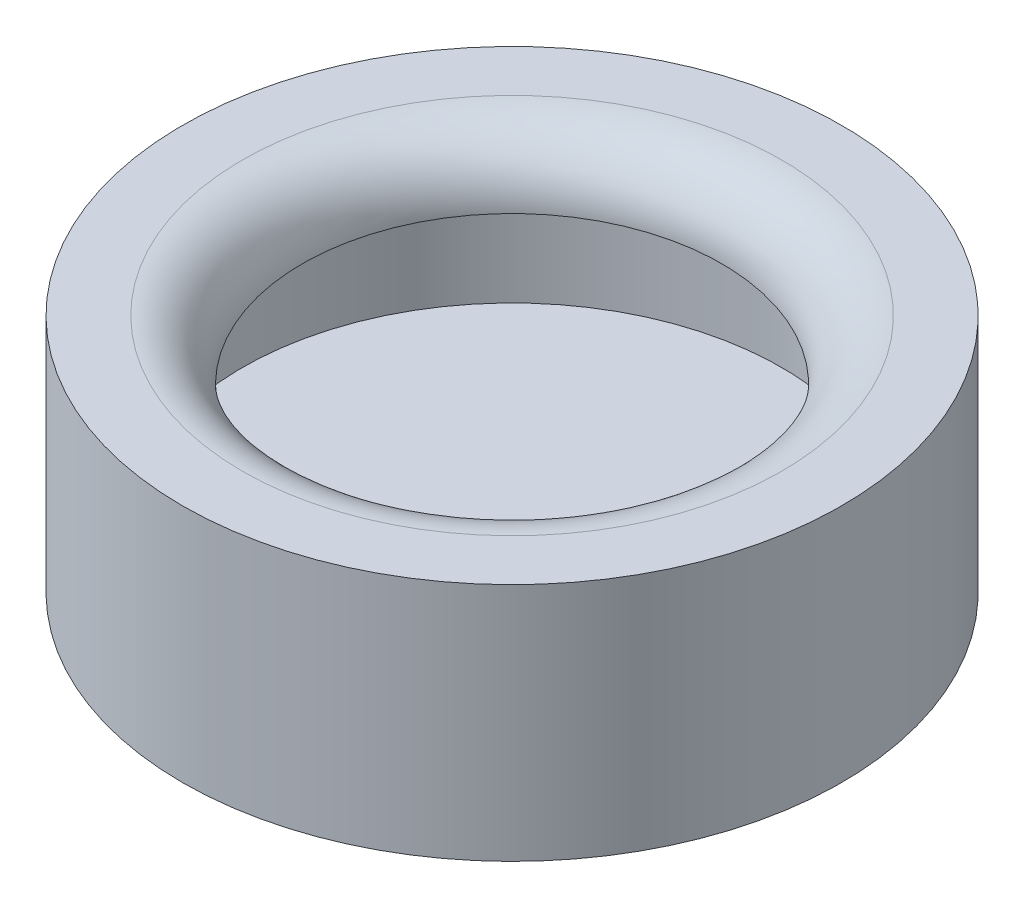
SolidWorks part; units mm, degrees
ref_plane "Front Plane" through (0, 0, 0) normal (0, 0, 1) x (1, 0, 0)
ref_plane "Top Plane" through (0, 0, 0) normal (0, 1, 0) x (1, 0, 0)
ref_plane "Right Plane" through (0, 0, 0) normal (1, 0, 0) x (0, 0, -1)
sketch "Sketch1" plane through (0, 0, 0) normal (0, 1, 0) x (1, 0, 0)
  circle A0 centre (0, 0) radius 6.985
  dimension "D1" = 13.97
extrude "Boss-Extrude1" add sketch "Sketch1" along normal blind 5.08
sketch "Sketch3" plane through (0, 5.08, 0) normal (0, 1, 0) x (1, 0, 0)
  circle A0 centre (0, 0) radius 5.08
  dimension "D1" = 10.16
extrude "Cut-Extrude1" cut sketch "Sketch3" against normal blind 3.81 contours A0
sketch "Sketch4" plane through (0, 5.08, 0) normal (0, 1, 0) x (1, 0, 0)
  circle A0 centre (0, 0) radius 5.08
  circle A1 centre (0, 0) radius 4.445
  dimension "D1" = 8.89
extrude "Boss-Extrude4" add sketch "Sketch4" against normal blind 3.81
fillet "Fillet2" radius 1.27 1 edges at (0, 5.08, 4.445)
sketch "Sketch5" plane through (0, 1.27, 0) normal (0, 1, 0) x (1, 0, 0)
  circle A0 centre (0, 0) radius 4.445
  circle A1 centre (0, 0) radius 5.715
extrude "Cut-Extrude2" cut sketch "Sketch5" along normal blind 2.54
